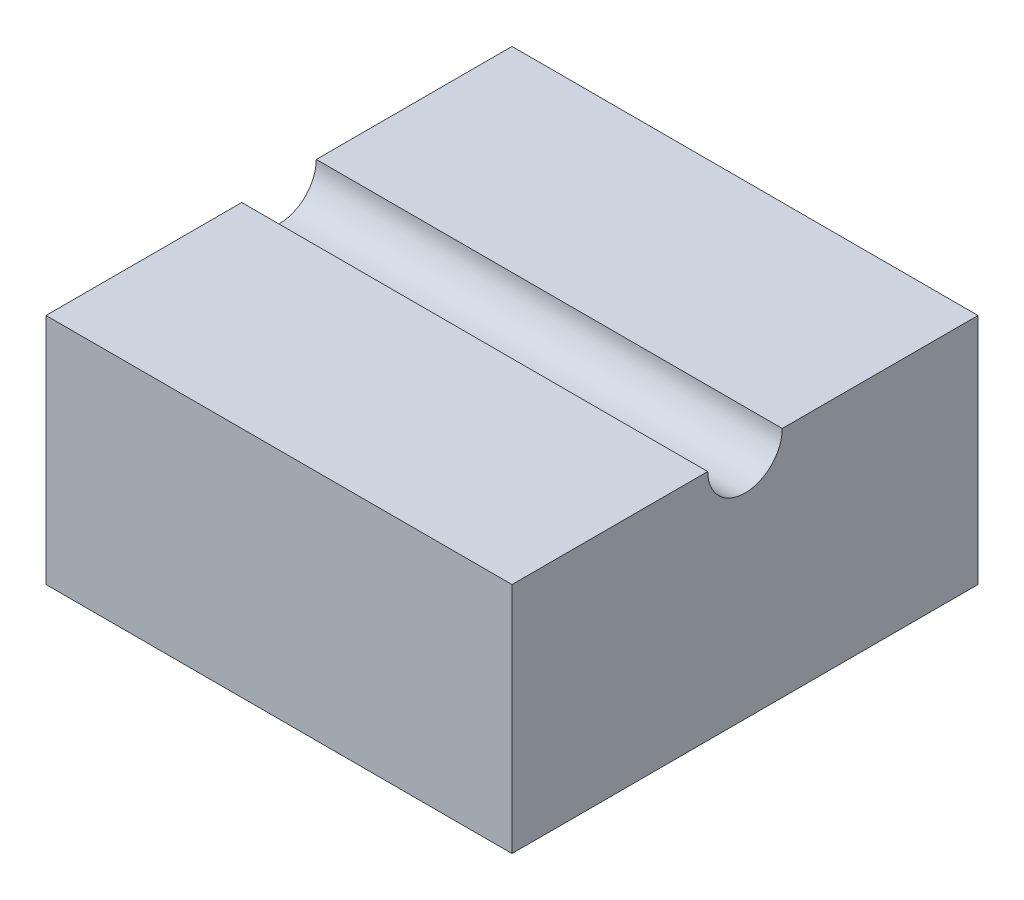
SolidWorks part; units mm, degrees
material "6061-T6 (SS)"
ref_plane "Front Plane" through (0, 0, 0) normal (0, 0, 1) x (1, 0, 0)
ref_plane "Top Plane" through (0, 0, 0) normal (0, 1, 0) x (1, 0, 0)
ref_plane "Right Plane" through (0, 0, 0) normal (1, 0, 0) x (0, 0, -1)
sketch "Sketch1" plane through (0, 0, 0) normal (0, 1, 0) x (1, 0, 0)
  line L1 (0, 0) -> (100, 0)
  line L2 (0, 0) -> (0, -100)
  line L3 (0, -100) -> (100, -100)
  line L4 (100, 0) -> (100, -100)
  line L5 (0, 0) -> (100, -100) construction
  line L6 (0, -100) -> (100, 0) construction
  point P4 (50, -50)
  dimension "D1" = 100
extrude "Boss-Extrude1" add sketch "Sketch1" along normal blind 50
sketch "Sketch2" plane through (100, 0, 0) normal (1, 0, 0) x (0, 0, -1)
  line L0 (-100, 50) -> (0, 50) construction
  circle A0 centre (-50, 50) radius 8
  dimension "D1" = 16
extrude "Cut-Extrude1" cut sketch "Sketch2" against normal through all
